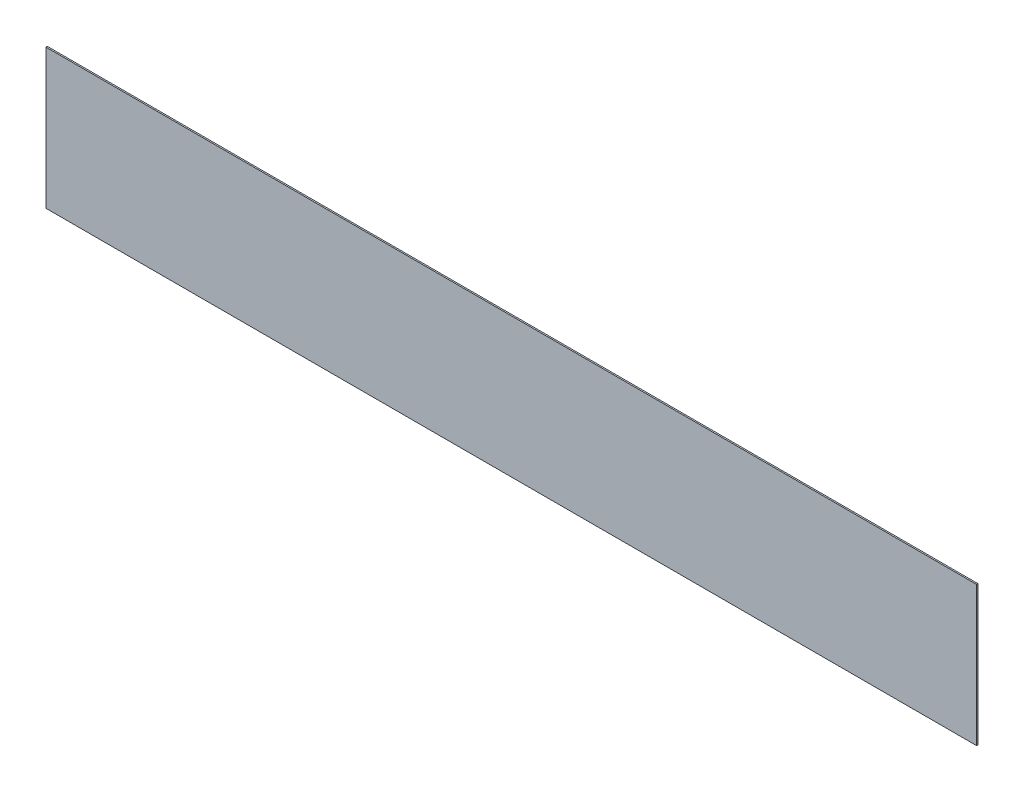
SolidWorks part; units mm, degrees
material "Copper"
ref_plane "Front Plane" through (0, 0, 0) normal (0, 0, 1) x (1, 0, 0)
ref_plane "Top Plane" through (0, 0, 0) normal (0, 1, 0) x (1, 0, 0)
ref_plane "Right Plane" through (0, 0, 0) normal (1, 0, 0) x (0, 0, -1)
sketch "Sketch1" plane through (0, 0, 0) normal (0, 0, 1) x (1, 0, 0)
  line L1 (-100, 15) -> (100, 15)
  line L2 (-100, 15) -> (-100, -15)
  line L3 (-100, -15) -> (100, -15)
  line L4 (100, 15) -> (100, -15)
  line L5 (-100, 15) -> (100, -15) construction
  line L6 (-100, -15) -> (100, 15) construction
  point P0 (0, 0)
  dimension "D1" = 30
  dimension "D2" = 200
extrude "Boss-Extrude1" add sketch "Sketch1" along normal blind 0.3
